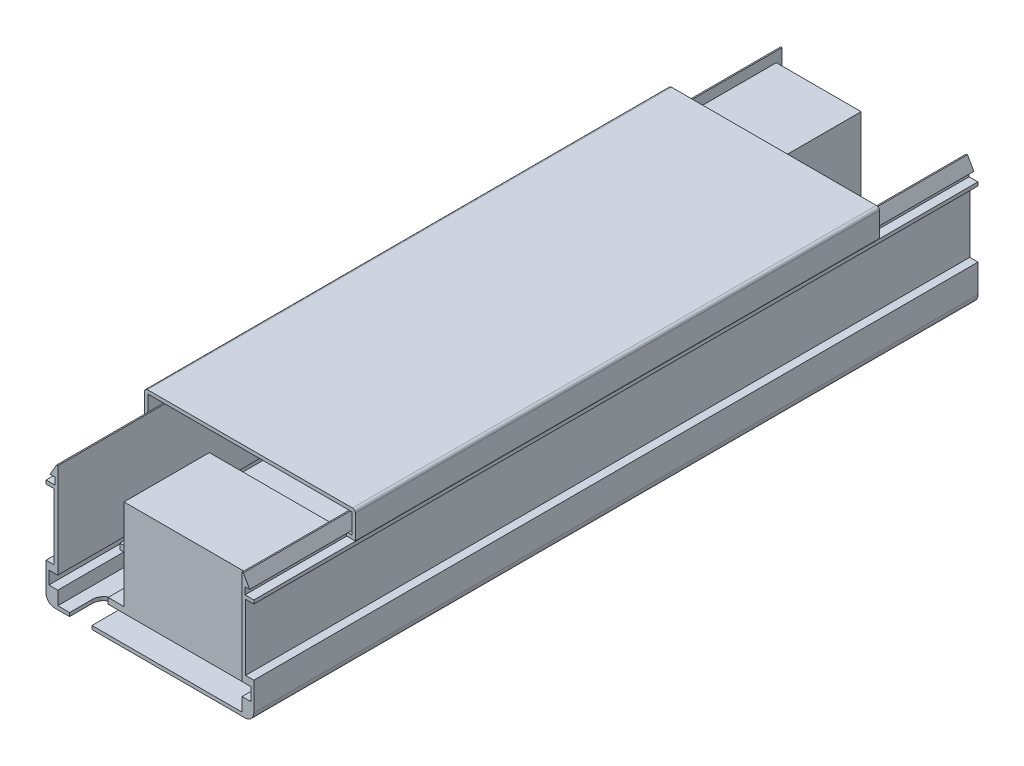
SolidWorks part; units mm, degrees
ref_plane "前基準面" through (0, 0, 0) normal (0, 0, 1) x (1, 0, 0)
ref_plane "上基準面" through (0, 0, 0) normal (0, 1, 0) x (1, 0, 0)
ref_plane "右基準面" through (0, 0, 0) normal (1, 0, 0) x (0, 0, -1)
sketch "草圖2" plane through (0, 0, 0) normal (0, 0, 1) x (1, 0, 0)
  line L0 (0, 25.7651) -> (0, -12.3745) construction
  line L1 (16.15, 0) -> (-16.15, 0)
  line L2 (-17.65, 1.5) -> (-17.65, 6.3)
  line L3 (-17.65, 6.3) -> (-16.25, 6.3)
  line L4 (-16.25, 6.3) -> (-16.25, 17.5)
  line L5 (-16.25, 17.5) -> (-17.65, 17.5)
  line L6 (-17.65, 17.5) -> (-17.65, 18.1)
  line L7 (-17.65, 18.1) -> (-16.15, 18.1)
  line L8 (-16.15, 18.1) -> (-16.15, 19.3)
  line L9 (-16.15, 19.3) -> (-16.95, 19.3)
  line L10 (-16.95, 19.3) -> (-15.86, 21.2)
  line L11 (-15.65, 21.2) -> (-15.65, 5.1)
  line L12 (-15.65, 5.1) -> (-17.15, 5.1)
  line L13 (-17.15, 5.1) -> (-17.15, 2.9)
  line L14 (-17.15, 2.9) -> (-15.65, 2.9)
  line L15 (-15.65, 2.9) -> (-15.65, 0.6)
  line L16 (-15.65, 0.6) -> (15.65, 0.6)
  line L17 (-15.86, 21.2) -> (-15.65, 21.2)
  line L18 (15.86, 21.2) -> (15.65, 21.2)
  line L19 (15.65, 2.9) -> (15.65, 0.6)
  line L20 (17.15, 2.9) -> (15.65, 2.9)
  line L21 (17.15, 5.1) -> (17.15, 2.9)
  line L22 (15.65, 5.1) -> (17.15, 5.1)
  line L23 (15.65, 21.2) -> (15.65, 5.1)
  line L24 (16.95, 19.3) -> (15.86, 21.2)
  line L25 (16.15, 19.3) -> (16.95, 19.3)
  line L26 (16.15, 18.1) -> (16.15, 19.3)
  line L27 (17.65, 18.1) -> (16.15, 18.1)
  line L28 (17.65, 17.5) -> (17.65, 18.1)
  line L29 (16.25, 17.5) -> (17.65, 17.5)
  line L30 (16.25, 6.3) -> (16.25, 17.5)
  line L31 (17.65, 6.3) -> (16.25, 6.3)
  line L32 (17.65, 1.5) -> (17.65, 6.3)
  arc A0 (-16.15, 0) -> (-17.65, 1.5) centre (-16.15, 1.5) cw
  arc A1 (16.15, 0) -> (17.65, 1.5) centre (16.15, 1.5) ccw
  point P29 (0, 0.6)
  point P41 (0, 0)
  dimension "D9" = 1.5
  dimension "D1" = 35.3
  dimension "D2" = 0.6
  dimension "D3" = 0.6
  dimension "D4" = 6.3
  dimension "D5" = 1.2
  dimension "D6" = 2.2
  dimension "D7" = 2
  dimension "D8" = 0.5
  dimension "D10" = 11.2
  dimension "D11" = 0.6
  dimension "D12" = 21.2
  dimension "D13" = 1.2
  dimension "D14" = 1.3
  dimension "D15" = 0.21
extrude "填料-伸長1" add sketch "草圖2" along normal mid plane 123
sketch "草圖3" plane through (0, 0, 0) normal (0, 0, 1) x (1, 0, 0)
  line L0 (0, -3.0217) -> (0, 28.6358) construction
  line L1 (17.4, 23) -> (-17.4, 23)
  line L2 (-17.9, 22.5) -> (-17.9, 18.4)
  line L3 (-17.9, 18.4) -> (-16.35, 18.4)
  line L4 (-16.35, 18.4) -> (-16.35, 19)
  line L5 (-16.35, 19) -> (-17.3, 19)
  line L6 (-17.3, 19) -> (-17.3, 22.4)
  line L7 (-17.3, 22.4) -> (17.3, 22.4)
  line L8 (-16.15, 0) -> (16.15, 0) construction
  line L9 (-16.15, 18.1) -> (-17.65, 18.1) construction
  line L10 (-16.15, 19.3) -> (-16.15, 18.1) construction
  line L11 (17.3, 19) -> (17.3, 22.4)
  line L12 (16.35, 19) -> (17.3, 19)
  line L13 (16.35, 18.4) -> (16.35, 19)
  line L14 (17.9, 18.4) -> (16.35, 18.4)
  line L15 (17.9, 22.5) -> (17.9, 18.4)
  arc A0 (-17.4, 23) -> (-17.9, 22.5) centre (-17.4, 22.5) ccw
  arc A1 (17.4, 23) -> (17.9, 22.5) centre (17.4, 22.5) cw
  point P3 (17.9, 23)
  point P13 (-17.3, 19.0589)
  point P14 (-16.3819, 19.0166)
  point P15 (-16.2736, 19.0995)
  point P22 (-17.9, 23)
  point P27 (0, 22.4)
  point P31 (0, 23)
  dimension "D8" = 0.5
  dimension "D1" = 35.8
  dimension "D2" = 23
  dimension "D3" = 0.6
  dimension "D4" = 0.6
  dimension "D5" = 0.6
  dimension "D6" = 0.3
  dimension "D7" = 0.2
extrude "填料-伸長2" add sketch "草圖3" along normal mid plane 89 separate body
sketch "草圖4" plane through (0, 0, 0) normal (0, 0, 1) x (1, 0, 0)
  line L0 (-17.15, 5.1) -> (-15.65, 5.1) construction
  line L1 (-15.6, 4.6) -> (15.6, 4.6)
  line L2 (-15.6, 4.6) -> (-15.6, 3.6)
  line L3 (-15.6, 3.6) -> (15.6, 3.6)
  line L4 (15.6, 4.6) -> (15.6, 3.6)
  point P6 (0, 3.6)
  dimension "D1" = 31.2
  dimension "D2" = 1
  dimension "D3" = 0.5
extrude "填料-伸長3" add sketch "草圖4" along normal mid plane 120 separate body
sketch "草圖5" plane through (0, 4.6, 0) normal (0, 1, 0) x (1, 0, 0)
  line L0 (15.6, 60) -> (-15.6, 60) construction
  line L1 (-15.1, 60) -> (-0.7, 60)
  line L2 (-15.1, 60) -> (-15.1, 45.5)
  line L3 (-15.1, 45.5) -> (-0.7, 45.5)
  line L4 (-0.7, 60) -> (-0.7, 45.5)
  line L5 (15.1, -60) -> (-5.9, -60)
  line L6 (15.1, -60) -> (15.1, -45.5)
  line L7 (15.1, -45.5) -> (-5.9, -45.5)
  line L8 (-5.9, -60) -> (-5.9, -45.5)
  line L9 (-15.6, -60) -> (-15.6, 60) construction
  line L10 (15.6, -60) -> (-15.6, -60) construction
  point P10 (-15.0735, 60)
  point P15 (14.9574, -60)
  dimension "D1" = 14.5
  dimension "D2" = 14.4
  dimension "D3" = 21
  dimension "D4" = 14.5
  dimension "D5" = 0.5
  dimension "D6" = 0.5
extrude "填料-伸長4" add sketch "草圖5" along normal blind 15.4
sketch "草圖6" plane through (0, 4.6, 0) normal (0, 1, 0) x (1, 0, 0)
  line L1 (15.6, 60) -> (8.6, 60)
  line L2 (15.6, 60) -> (15.6, 51)
  line L3 (15.6, 51) -> (8.6, 51)
  line L4 (8.6, 60) -> (8.6, 51)
  line L5 (-15.6, -60) -> (-8.6, -60)
  line L6 (-15.6, -60) -> (-15.6, -51)
  line L7 (-15.6, -51) -> (-8.6, -51)
  line L8 (-8.6, -60) -> (-8.6, -51)
  dimension "D1" = 7
  dimension "D2" = 9
  dimension "D3" = 7
  dimension "D4" = 9
extrude "除料-伸長1" cut sketch "草圖6" against normal through all
sketch "草圖7" plane through (0, 0.6, 0) normal (0, 1, 0) x (1, 0, 0)
  line L0 (9.35, 61.5) -> (13.15, 61.5)
  line L1 (15.65, 61.5) -> (-15.65, 61.5) construction
  line L2 (13.15, 61.5) -> (13.15, 57.6)
  line L3 (9.35, 57.6) -> (9.35, 61.5)
  line L4 (17.65, -61.5) -> (17.65, 61.5) construction
  line L5 (-13.65, -61.5) -> (-13.65, -57.6)
  line L6 (15.65, -61.5) -> (-15.65, -61.5) construction
  line L7 (-9.85, -57.6) -> (-9.85, -61.5)
  line L8 (-9.85, -61.5) -> (-13.65, -61.5)
  line L9 (-17.65, -61.5) -> (-17.65, 61.5) construction
  arc A0 (13.15, 57.6) -> (9.35, 57.6) centre (11.25, 57.6) cw
  arc A1 (-13.65, -57.6) -> (-9.85, -57.6) centre (-11.75, -57.6) cw
  point P9 (11.25, 55.7)
  point P19 (-11.75, -55.7)
  dimension "D1" = 3.8
  dimension "D2" = 4.5
  dimension "D3" = 5.8
  dimension "D4" = 4
  dimension "D5" = 3.8
  dimension "D6" = 5.8
extrude "除料-伸長2" cut sketch "草圖7" against normal through all
